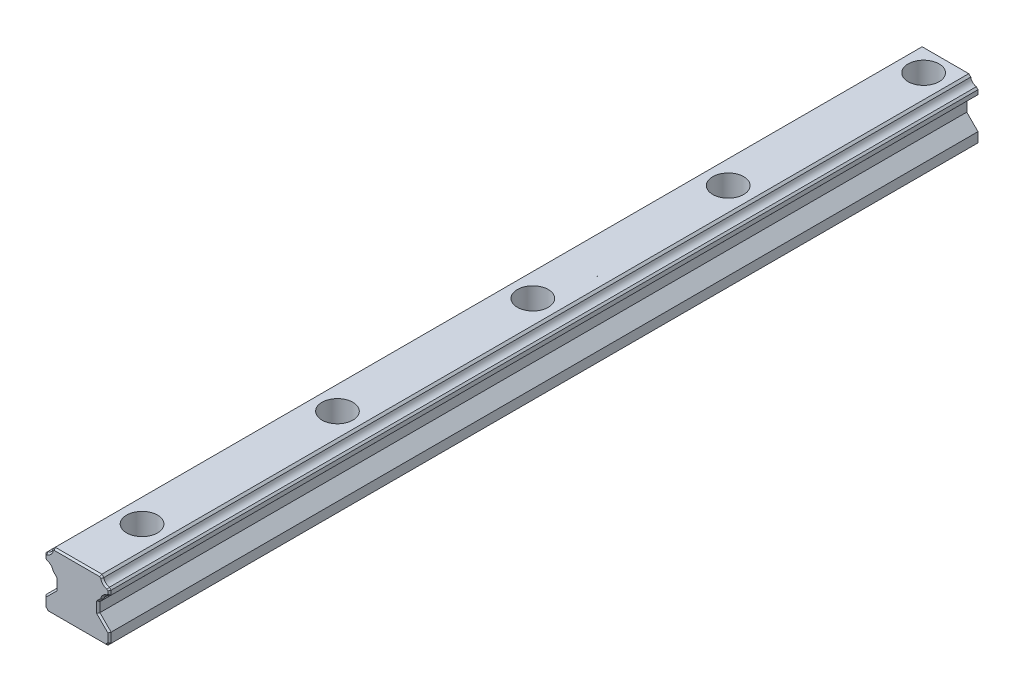
SolidWorks part; units mm, degrees
ref_plane "Front Plane" through (0, 0, 0) normal (0, 0, 1) x (1, 0, 0)
ref_plane "Top Plane" through (0, 0, 0) normal (0, 1, 0) x (1, 0, 0)
ref_plane "Right Plane" through (0, 0, 0) normal (1, 0, 0) x (0, 0, -1)
sketch "Sketch1" plane through (-20, 0, 0) normal (0, 0, 1) x (1, 0, 0)
  line L0 (10, -4.9999) -> (10, -8)
  line L1 (10, -8) -> (11, -9)
  line L2 (11, -9) -> (20, -9)
  line L3 (17, 9) -> (23, 9)
  line L5 (26.55, -1.55) -> (30, -4.9999)
  line L6 (26.55, 1.3792) -> (26.55, -1.55)
  line L7 (27.7679, 2.5951) -> (26.55, 1.3792)
  line L8 (30, 4.8292) -> (29.4727, 4.3144)
  line L9 (30, 6.16) -> (30, 4.8292)
  line L10 (29.4727, 6.6874) -> (30, 6.16)
  line L11 (27.16, 9) -> (27.7679, 8.3921)
  line L13 (29, -9) -> (20, -9)
  line L14 (30, -8) -> (29, -9)
  line L15 (30, -4.9999) -> (30, -8)
  line L16 (27.16, 9) -> (12.84, 9)
  line L17 (12.84, 9) -> (12.2321, 8.3921)
  line L18 (10.5273, 6.6874) -> (10, 6.16)
  line L19 (10, 6.16) -> (10, 4.8292)
  line L20 (10, 4.8292) -> (10.5273, 4.3144)
  line L21 (12.2321, 2.5951) -> (13.45, 1.3792)
  line L22 (13.45, 1.3792) -> (13.45, -1.55)
  line L23 (13.45, -1.55) -> (10, -4.9999)
  line L25 (20, -9) -> (20, 9) construction
  arc A0 (29.4727, 4.3144) -> (27.7679, 2.5951) centre (29.8039, 2.2812) ccw
  arc A1 (27.7679, 8.3921) -> (29.4727, 6.6874) centre (29.8015, 8.7209) ccw
  arc A2 (12.2321, 8.3921) -> (10.5273, 6.6874) centre (10.1985, 8.7209) cw
  arc A3 (10.5273, 4.3144) -> (12.2321, 2.5951) centre (10.1961, 2.2812) cw
  point P3 (20, 0.5)
  point P37 (20, 0)
  point P42 (20, 9)
  dimension "D17" = 2.06
  dimension "Rail Width" = 20
  dimension "D2" = 1
  dimension "D3" = 1
  dimension "D4" = 6
  dimension "D7" = 18
  dimension "D8" = 4.0001
  dimension "D9" = 10.55
  dimension "D10" = 13.1001
  dimension "D11" = 15.5359
  dimension "D12" = 0.6079
  dimension "D13" = 0.6079
  dimension "D15" = 0.5273
  dimension "D16" = 0.5273
  dimension "D18" = 1.2159
  dimension "D19" = 0.5148
  dimension "D20" = 6.4049
  dimension "D21" = 2.84
  dimension "D22" = 4.1708
  dimension "Rail Height" = 18
  dimension "Mounting Hole Dpeth" = 8.5
sketch "Sketch2" plane through (0, 0, 0) normal (1, 0, 0) x (0, 0, -1)
  line L0 (-120, 9) -> (-115.25, 9)
  line L1 (-115.25, 9) -> (-115.25, 0.5)
  line L2 (-115.25, 0.5) -> (-117, 0.5)
  line L3 (-117, 0.5) -> (-117, -9)
  line L4 (-117, -9) -> (-120, -9)
  line L5 (-120, -9) -> (-120, 9) construction
  line L6 (-120, -9) -> (-120, 9) construction
  line L7 (50, 0) -> (-50, 0)
  line L9 (-120, 9) -> (-120, -9)
  line L10 (140, 0) -> (-140, 0) construction
  point P6 (0, 0)
  point P7 (-120, 0)
  point P8 (60, 0)
  point P11 (0, 0)
  point P12 (-60, 0)
  point P14 (-50, 0)
  point P21 (0, 0)
  point P22 (50, 0)
  point P24 (120, 0)
  point P35 (50, -1)
  dimension "D1" = 9.5
  dimension "Rail Length" = 280
  dimension "Mounting Hole Center-to-End" = 20
  dimension "Mounting Hole Center-to-Center" = 60
  dimension "D2" = 90
  dimension "D4" = 1
  dimension "Number of Mounting Holes" = 5
sketch "Sketch3" plane through (0, 0, 0) normal (0, 0, 1) x (1, 0, 0)
  line L0 (-3, 9) -> (3, 9) construction
  line L3 (-3, 9) -> (3, 9)
  line L21 (0, -9) -> (9, -9)
  line L22 (9, -9) -> (10, -8)
  line L23 (10, -8) -> (10, -4.9999)
  line L24 (10, -4.9999) -> (6.55, -1.55)
  line L25 (6.55, -1.55) -> (6.55, 1.3792)
  line L26 (6.55, 1.3792) -> (7.7679, 2.5951)
  line L27 (9.4727, 4.3144) -> (10, 4.8292)
  line L28 (10, 4.8292) -> (10, 6.16)
  line L29 (10, 6.16) -> (9.4727, 6.6874)
  line L30 (7.7679, 8.3921) -> (7.16, 9)
  line L31 (7.16, 9) -> (-7.16, 9)
  line L32 (-7.16, 9) -> (-7.7679, 8.3921)
  line L33 (-9.4727, 6.6874) -> (-10, 6.16)
  line L34 (-10, 6.16) -> (-10, 4.8292)
  line L35 (-10, 4.8292) -> (-9.4727, 4.3144)
  line L36 (-7.7679, 2.5951) -> (-6.55, 1.3792)
  line L37 (-6.55, 1.3792) -> (-6.55, -1.55)
  line L38 (-6.55, -1.55) -> (-10, -4.9999)
  line L39 (-10, -4.9999) -> (-10, -8)
  line L40 (-10, -8) -> (-9, -9)
  line L41 (-9, -9) -> (0, -9)
  line L42 (0, -9) -> (9, -9)
  line L43 (9, -9) -> (10, -8)
  line L44 (10, -8) -> (10, -4.9999)
  line L45 (10, -4.9999) -> (6.55, -1.55)
  line L46 (6.55, -1.55) -> (6.55, 1.3792)
  line L47 (6.55, 1.3792) -> (7.7679, 2.5951)
  line L48 (9.4727, 4.3144) -> (10, 4.8292)
  line L49 (10, 4.8292) -> (10, 6.16)
  line L50 (10, 6.16) -> (9.4727, 6.6874)
  line L51 (7.7679, 8.3921) -> (7.16, 9)
  line L52 (7.16, 9) -> (-7.16, 9)
  line L53 (-7.16, 9) -> (-7.7679, 8.3921)
  line L54 (-9.4727, 6.6874) -> (-10, 6.16)
  line L55 (-10, 6.16) -> (-10, 4.8292)
  line L56 (-10, 4.8292) -> (-9.4727, 4.3144)
  line L57 (-7.7679, 2.5951) -> (-6.55, 1.3792)
  line L58 (-6.55, 1.3792) -> (-6.55, -1.55)
  line L59 (-6.55, -1.55) -> (-10, -4.9999)
  line L60 (-10, -4.9999) -> (-10, -8)
  line L61 (-10, -8) -> (-9, -9)
  line L62 (-9, -9) -> (0, -9)
  arc A4 (9.4727, 4.3144) -> (7.7679, 2.5951) centre (9.8039, 2.2812) ccw
  arc A5 (7.7679, 8.3921) -> (9.4727, 6.6874) centre (9.8015, 8.7209) ccw
  arc A6 (-9.4727, 6.6874) -> (-7.7679, 8.3921) centre (-9.8015, 8.7209) ccw
  arc A7 (-7.7679, 2.5951) -> (-9.4727, 4.3144) centre (-9.8039, 2.2812) ccw
  arc A8 (9.4727, 4.3144) -> (7.7679, 2.5951) centre (9.8039, 2.2812) ccw
  arc A9 (7.7679, 8.3921) -> (9.4727, 6.6874) centre (9.8015, 8.7209) ccw
  arc A10 (-9.4727, 6.6874) -> (-7.7679, 8.3921) centre (-9.8015, 8.7209) ccw
  arc A11 (-7.7679, 2.5951) -> (-9.4727, 4.3144) centre (-9.8039, 2.2812) ccw
  dimension "D1" = 0
extrude "Boss-Extrude1" add sketch "Sketch3" along normal up to vertex (140 mm away) and the other way up to vertex (140 mm away) contours A11 L57 L58 L59 L60 L61 L62 L42 L43 L44 L45 L46 L47 A8 L48 L49 L50 A9 L51 L52 L3 L53 A10 L54 L55 L56 up to point (0, 0, 140) other way up to point (0, 0, -140)
sketch "Sketch4" plane through (0, 0, 0) normal (1, 0, 0) x (0, 0, -1)
  line L6 (-115.25, 9) -> (-120, 9)
  line L7 (-115.25, 0.5) -> (-115.25, 9)
  line L8 (-117, 0.5) -> (-115.25, 0.5)
  line L9 (-117, -9) -> (-117, 0.5)
  line L10 (-120, -9) -> (-117, -9)
  line L11 (-120, 9) -> (-120, -9)
  line L12 (-115.25, 9) -> (-120, 9)
  line L13 (-115.25, 0.5) -> (-115.25, 9)
  line L14 (-117, 0.5) -> (-115.25, 0.5)
  line L15 (-117, -9) -> (-117, 0.5)
  line L16 (-120, -9) -> (-117, -9)
  line L17 (-120, 9) -> (-120, -9)
  dimension "D1" = 0
revolve "Cut-Revolve1" cut sketch "Sketch4" angle 360 about L17
pattern_linear "LPattern2" count 5 spacing 60 along (0, 0, -1) of "Cut-Revolve1"
sketch "Sketch5" plane through (0, 0, 0) normal (0, 1, 0) x (1, 0, 0)
  line L0 (3, -120) -> (0, -120) construction
  line L1 (0, -120) -> (2.1213, -117.8787) construction
  circle A1 centre (0, -120) radius 3 construction
  circle A2 centre (0, -120) radius 3 construction
  point P3 (0, -123)
  point P4 (-3, -120)
  point P6 (3, -120)
  point P7 (2.1213, -117.8787)
  dimension "D1" = 45
sketch "Sketch6" plane through (0, 0, 0) normal (0, 0, 1) x (1, 0, 0)
  line L0 (4.75, 9) -> (-4.75, 9) construction
  line L1 (3, 0.5) -> (-3, 0.5) construction
  line L2 (4.75, 9) -> (-4.75, 9) construction
  line L3 (3, 0.5) -> (-3, 0.5) construction
  line L4 (-4.75, 9) -> (-4.75, 0.5)
  line L5 (-4.75, 0.5) -> (-3, 0.5)
  line L6 (4.75, 9) -> (4.75, 0.5)
  line L7 (4.75, 0.5) -> (3, 0.5)
  line L8 (3, 0.5) -> (3, -9)
  line L9 (-9, -9) -> (9, -9) construction
  line L10 (-3, 0.5) -> (-3, -9)
chamfer "Chamfer1" distance 0.5 angle 45 48 edges at (-7.159, 1.9872, -140) (-6.55, -0.0854, -140) (-8.275, -3.275, -140) (-10, -6.5, -140) (-9.5, -8.5, -140) (0, -9, -140) (9.5, -8.5, -140) (10, -6.5, -140) (8.275, -3.275, -140) (6.55, -0.0854, -140) (7.159, 1.9872, -140) (8.3411, 3.7316, -140) (9.7363, 4.5718, -140) (10, 5.4946, -140) (9.7363, 6.4237, -140) (8.3449, 7.2643, -140) (7.464, 8.6961, -140) (0, 9, -140) (-7.464, 8.6961, -140) (-8.3449, 7.2643, -140) (-9.7363, 6.4237, -140) (-10, 5.4946, -140) (-9.7363, 4.5718, -140) (-8.3411, 3.7316, -140) (-9.7363, 4.5718, 140) (-10, 5.4946, 140) (-9.7363, 6.4237, 140) (-8.3449, 7.2643, 140) (-7.464, 8.6961, 140) (0, 9, 140) (7.464, 8.6961, 140) (8.3449, 7.2643, 140) (9.7363, 6.4237, 140) (10, 5.4946, 140) (9.7363, 4.5718, 140) (8.3411, 3.7316, 140) (7.159, 1.9872, 140) (6.55, -0.0854, 140) (8.275, -3.275, 140) (10, -6.5, 140) (9.5, -8.5, 140) (0, -9, 140) (-9.5, -8.5, 140) (-10, -6.5, 140) (-8.275, -3.275, 140) (-6.55, -0.0854, 140) (-7.159, 1.9872, 140) (-8.3411, 3.7316, 140)
sketch "Sketch7" plane through (0, -9, 0) normal (0, -1, 0) x (1, 0, 0)
  line L0 (15.69, -126.7) -> (-26.1609, -126.7)
  line L1 (-9.4958, -126.7) -> (-14.3167, -126.7) construction
extrude "Cut-Extrude1" cut sketch "Sketch7" against normal through all and the other way through all
equation "\"D3@LPattern2\"=\"Mounting Hole Center-to-Center@Sketch2\""
equation "\"D1@LPattern2\"=\"Number of Mounting Holes@Sketch2\""
